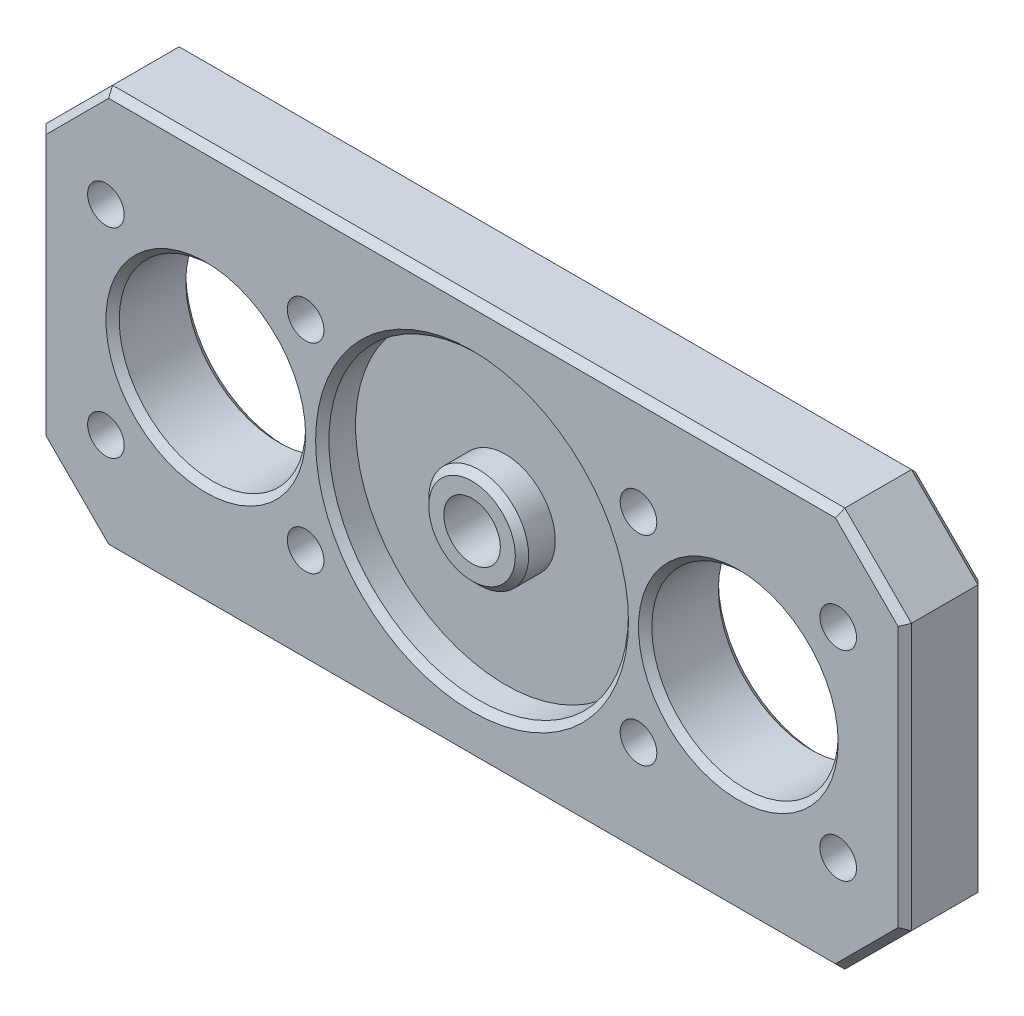
SolidWorks part; units mm, degrees
material "Q235-A"
ref_plane "前视基准面" through (0, 0, 0) normal (0, 0, 1) x (1, 0, 0)
ref_plane "上视基准面" through (0, 0, 0) normal (0, 1, 0) x (1, 0, 0)
ref_plane "右视基准面" through (0, 0, 0) normal (1, 0, 0) x (0, 0, -1)
sketch "草图1" plane through (0, 0, 0) normal (0, 0, 1) x (1, 0, 0)
  line L1 (-65, 30) -> (65, 30)
  line L2 (-65, 30) -> (-65, -30)
  line L3 (-65, -30) -> (65, -30)
  line L4 (65, 30) -> (65, -30)
  line L5 (-65, 30) -> (65, -30) construction
  line L6 (-65, -30) -> (65, 30) construction
  point P0 (0, 0)
  dimension "D1" = 130
  dimension "D2" = 60
extrude "凸台-拉伸1" add sketch "草图1" along normal blind 12
sketch "草图4" plane through (0, 0, 0) normal (0, 0, -1) x (-1, 0, 0)
  circle A0 centre (0, 0) radius 16.5
  dimension "D1" = 33
extrude "凸台-拉伸2" add sketch "草图4" along normal blind 6
hole_wizard "M10 螺纹孔1" positions "草图2" profile "草图3" tap size "M10" standard "GB"
sketch "草图2" plane through (0, 0, -6) normal (0, 0, -1) x (-1, 0, 0)
  point P0 (0, 0)
sketch "草图3" plane through (0, 0, -6) normal (1, 0, 0) x (0, 1, 0)
  line L0 (0, 0) -> (0, 27.0537)
  line L1 (0, 27.0537) -> (4.25, 24.5)
  line L2 (4.25, 24.5) -> (4.25, 0)
  line L5 (4.25, 0) -> (0, 0)
  line L10 (0, 27.0537) -> (-4.25, 24.5) construction
  line L11 (0, -6.35) -> (0, 107.95) construction
  dimension "螺纹孔钻头直径" = 8.5
  dimension "螺纹孔钻头深度" = 24.5
  dimension "导头角度" = 118
cosmetic thread "孔螺蚊线2" parameters "D1"=20, "D2"=10
hole_wizard "打孔尺寸(%根据)内六角圆柱头螺钉的类型1" positions "草图5" profile "草图6" counterbore size "M5" standard "GB"
sketch "草图5" plane through (0, 0, 0) normal (0, 0, -1) x (-1, 0, 0)
  line L7 (0, 0) -> (-40, 0) construction
  line L10 (-55, 15) -> (-25, 15) construction
  line L11 (-55, 15) -> (-55, -15) construction
  line L12 (-55, -15) -> (-25, -15) construction
  line L13 (-25, 15) -> (-25, -15) construction
  line L14 (-55, 15) -> (-25, -15) construction
  line L15 (-55, -15) -> (-25, 15) construction
  line L16 (0, 0) -> (40, 0) construction
  line L19 (25, 15) -> (55, 15) construction
  line L20 (25, 15) -> (25, -15) construction
  line L21 (25, -15) -> (55, -15) construction
  line L22 (55, 15) -> (55, -15) construction
  line L23 (25, 15) -> (55, -15) construction
  line L24 (25, -15) -> (55, 15) construction
  point P0 (-55, 15)
  point P2 (-55, -15)
  point P4 (-25, 15)
  point P6 (-25, -15)
  point P180 (-40, 0)
  point P191 (55, -15)
  point P380 (25, 15)
  point P381 (25, -15)
  point P382 (55, 15)
  point P385 (40, 0)
  dimension "D1" = 40
  dimension "D2" = 30
  dimension "D3" = 30
sketch "草图6" plane through (55, 15, 0) normal (1, 0, 0) x (0, 1, 0)
  line L0 (0, 0) -> (0, 16.6524)
  line L1 (0, 16.6524) -> (2.75, 15)
  line L2 (2.75, 15) -> (2.75, 5.7)
  line L3 (2.75, 5.7) -> (5, 5.7)
  line L4 (5, 5.7) -> (5, 0)
  line L5 (5, 0) -> (0, 0)
  line L10 (0, 16.6524) -> (-2.75, 15) construction
  line L11 (0, -6.35) -> (0, 107.95) construction
  dimension "孔直径" = 5.5
  dimension "孔深度" = 15
  dimension "柱形沉头孔直径" = 10
  dimension "柱形沉头孔深度" = 5.7
  dimension "导头角度" = 118
chamfer "倒角1" distance 10 angle 45 4 edges at (-65, -30, 6) (-65, 30, 6) (65, -30, 6) (65, 30, 6)
chamfer "倒角2" distance 1 angle 45 16 edges at (60, -25, 0) (65, 0, 0) (60, 25, 0) (0, 30, 0) (-60, 25, 0) (-65, 0, 0) (-60, -25, 0) (0, -30, 0) (60, 25, 12) (65, 0, 12) (60, -25, 12) (0, -30, 12) (-60, -25, 12) (-65, 0, 12) (-60, 25, 12) (0, 30, 12)
sketch "草图7" plane through (0, 0, 0) normal (0, 0, -1) x (-1, 0, 0)
  line L0 (-55, 15) -> (-25, -15) construction
  line L1 (25, 15) -> (55, -15) construction
  circle A0 centre (-40, 0) radius 14
  circle A1 centre (40, 0) radius 14
  dimension "D1" = 28
extrude "切除-拉伸1" cut sketch "草图7" against normal through all
chamfer "倒角3" distance 1 angle 45 4 edges at (-54, 0, 0) (-54, 0, 12) (26, 0, 0) (26, 0, 12)
sketch "草图8" plane through (0, 0, 12) normal (0, 0, 1) x (1, 0, 0)
  circle A0 centre (0, 0) radius 7.5
  circle A1 centre (0, 0) radius 22.5
  dimension "D1" = 15
  dimension "D2" = 15
extrude "切除-拉伸2" cut sketch "草图8" against normal blind 5
chamfer "倒角4" distance 1 angle 45 2 edges at (7.5, 0, 12) (22.5, 0, 12)
